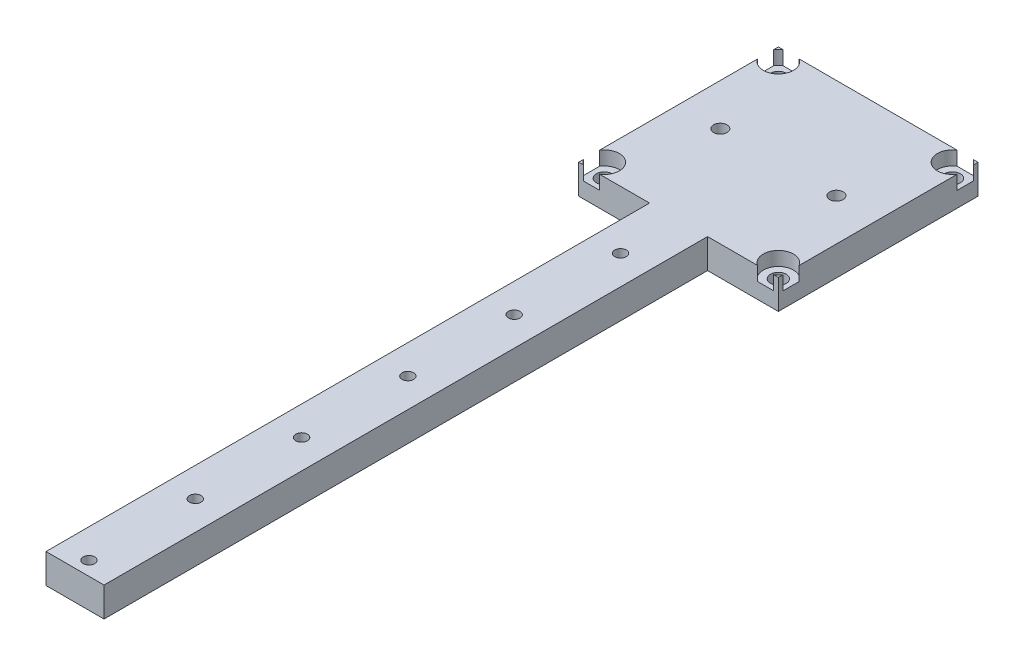
SolidWorks part; units mm, degrees
ref_plane "Front Plane" through (0, 0, 0) normal (0, 0, 1) x (1, 0, 0)
ref_plane "Top Plane" through (0, 0, 0) normal (0, 1, 0) x (1, 0, 0)
ref_plane "Right Plane" through (0, 0, 0) normal (1, 0, 0) x (0, 0, -1)
sketch "Sketch2" plane through (0, 0, 0) normal (0, 1, 0) x (1, 0, 0)
  line L0 (-6.25, -21.5) -> (-21.5, -21.5)
  line L1 (6.25, -21.5) -> (21.5, -21.5)
  line L2 (-21.5, -21.5) -> (-21.5, 21.5)
  line L3 (-21.5, 21.5) -> (21.5, 21.5)
  line L4 (21.5, -21.5) -> (21.5, 21.5)
  line L5 (-21.5, -21.5) -> (21.5, 21.5) construction
  line L6 (-21.5, 21.5) -> (21.5, -21.5) construction
  line L7 (-6.25, -21.5) -> (-6.25, -151.5)
  line L8 (-6.25, -151.5) -> (6.25, -151.5)
  line L9 (6.25, -21.5) -> (6.25, -151.5)
  point P0 (0, 0)
  dimension "D1" = 43
  dimension "D2" = 43
  dimension "D3" = 12.5
  dimension "D4" = 15.25
  dimension "D5" = 130
extrude "Extrude1" add sketch "Sketch2" along normal blind 6.35
sketch "Sketch4" plane through (0, 6.35, 0) normal (0, 1, 0) x (-1, 0, 0)
  line L0 (0, 158.7405) -> (0, -28.5215) construction
  line L1 (31.3198, 0) -> (-31.5389, 0) construction
hole_wizard "M3x0.5 Tapped Hole1" positions "3DSketch2" profile "Sketch5" tap size "M3x0.5" standard "Ansi Metric"
sketch3d "3DSketch2"
  line L0 (0, 6.35, 158.7405) -> (0, 6.35, -28.5215) construction
  line L1 (-6.25, 6.35, 151.5) -> (6.25, 6.35, 151.5) construction
  point P0 (0, 6.35, 148.5)
  dimension "D1" = 3
sketch "Sketch5" plane through (0, 6.35, 148.5) normal (1, 0, 0) x (0, 0, 1)
  line L0 (0, 0) -> (0, 8.2511)
  line L1 (0, 8.2511) -> (1.25, 7.5)
  line L2 (1.25, 7.5) -> (1.25, 0)
  line L5 (1.25, 0) -> (0, 0)
  line L10 (0, 8.2511) -> (-1.25, 7.5) construction
  line L11 (0, -6.35) -> (0, 107.95) construction
  dimension "Tap Drill Dia." = 2.5
  dimension "Tap Drill Depth" = 7.5
  dimension "Drill Angle" = 118
pattern_linear "LPattern1" count 6 spacing 22.9 along (0, 0, -1) of "M3x0.5 Tapped Hole1"
hole_wizard "CBORE for M3 SHCS1" positions "3DSketch3" profile "Sketch6" counterbore size "M3" standard "Ansi Metric" end condition through all
sketch3d "3DSketch3"
  line L0 (-31.3198, 6.35, 0) -> (31.5389, 6.35, 0) construction
  line L1 (0, 6.35, 158.7405) -> (0, 6.35, -28.5215) construction
  point P0 (-18.75, 6.35, -18.75)
  dimension "D1" = 18.75
  dimension "D2" = 18.75
sketch "Sketch6" plane through (-18.75, 6.35, -18.75) normal (1, 0, 0) x (0, 0, 1)
  line L0 (0, 0) -> (0, 6.35)
  line L1 (0, 6.35) -> (1.7, 6.35)
  line L3 (1.7, 6.35) -> (1.7, 3)
  line L4 (1.7, 3) -> (3.25, 3)
  line L5 (3.25, 3) -> (3.25, 0)
  line L7 (3.25, 0) -> (0, 0)
  line L11 (0, -6.35) -> (0, 107.95) construction
  dimension "Thru Hole Dia." = 3.4
  dimension "Thru Hole Depth" = 6.35
  dimension "C'Bore Dia." = 6.5
  dimension "C'Bore Depth" = 3
pattern_linear "LPattern2" count 2 spacing 37.5 along (1, 0, 0) count 2 spacing 37.5 along (0, 0, 1) of "CBORE for M3 SHCS1"
hole_wizard "Ø2.9 (2.9) Diameter Hole1" positions "3DSketch4" profile "Sketch7" hole size "Ø2.9" standard "Ansi Metric" end condition through all
sketch3d "3DSketch4"
  line L0 (-31.3198, 6.35, 0) -> (31.5389, 6.35, 0) construction
  line L1 (0, 6.35, 158.7405) -> (0, 6.35, -28.5215) construction
  point P0 (-12.5, 6.35, 0)
  point P4 (12.5, 6.35, 0)
  dimension "D1" = 12.5
  dimension "D2" = 12.5
sketch "Sketch7" plane through (-12.5, 6.35, 0) normal (1, 0, 0) x (0, 0, 1)
  line L0 (0, 0) -> (0, 6.35)
  line L1 (0, 6.35) -> (1.45, 6.35)
  line L2 (1.45, 6.35) -> (1.45, 0)
  line L5 (1.45, 0) -> (0, 0)
  line L11 (0, -6.35) -> (0, 107.95) construction
  dimension "Thru Hole Dia." = 2.9
  dimension "Thru Hole Depth" = 6.35
